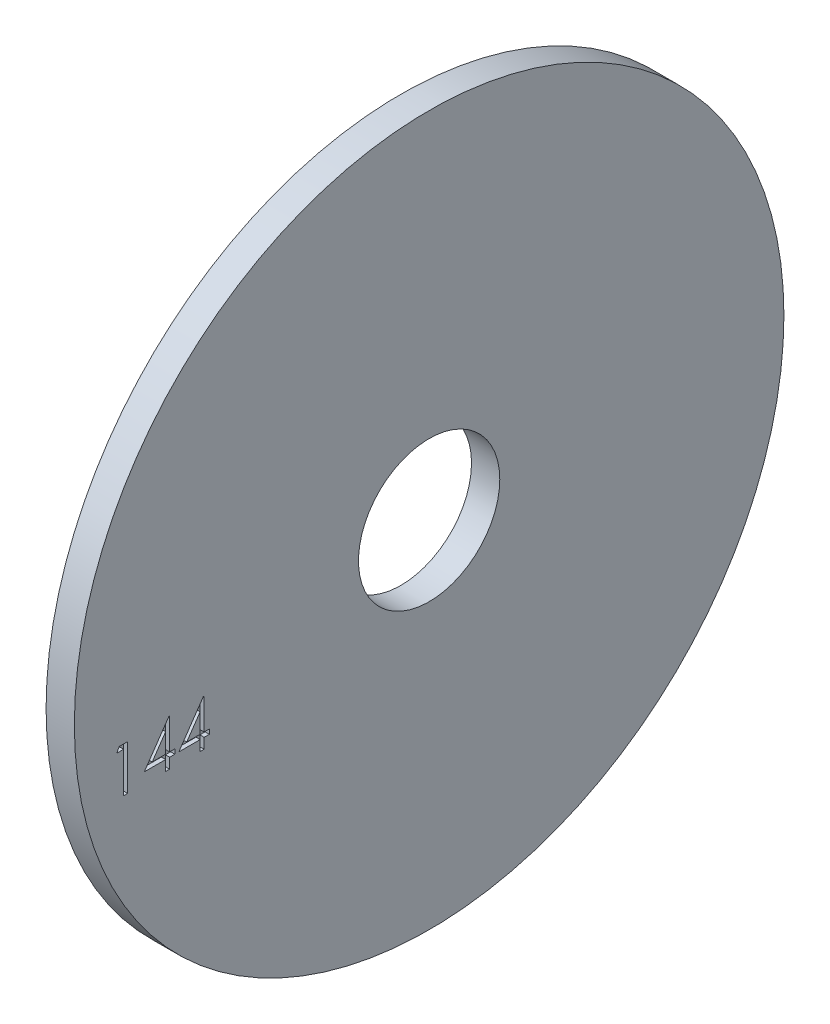
SolidWorks part; units mm, degrees
ref_plane "Front Plane" through (0, 0, 0) normal (0, 0, 1) x (1, 0, 0)
ref_plane "Top Plane" through (0, 0, 0) normal (0, 1, 0) x (1, 0, 0)
ref_plane "Right Plane" through (0, 0, 0) normal (1, 0, 0) x (0, 0, -1)
sketch "Sketch1" plane through (0, 0, 0) normal (1, 0, 0) x (0, 0, -1)
  circle A0 centre (0, 0) radius 25.11
  circle A1 centre (0, 0) radius 5
extrude "Boss-Extrude1" add sketch "Sketch1" along normal blind 2
sketch "Sketch3" plane through (2, 0, 0) normal (1, 0, 0) x (0, 0, -1)
  text T0 "144"
extrude "Cut-Extrude2" cut sketch "Sketch3" against normal blind 0.3
